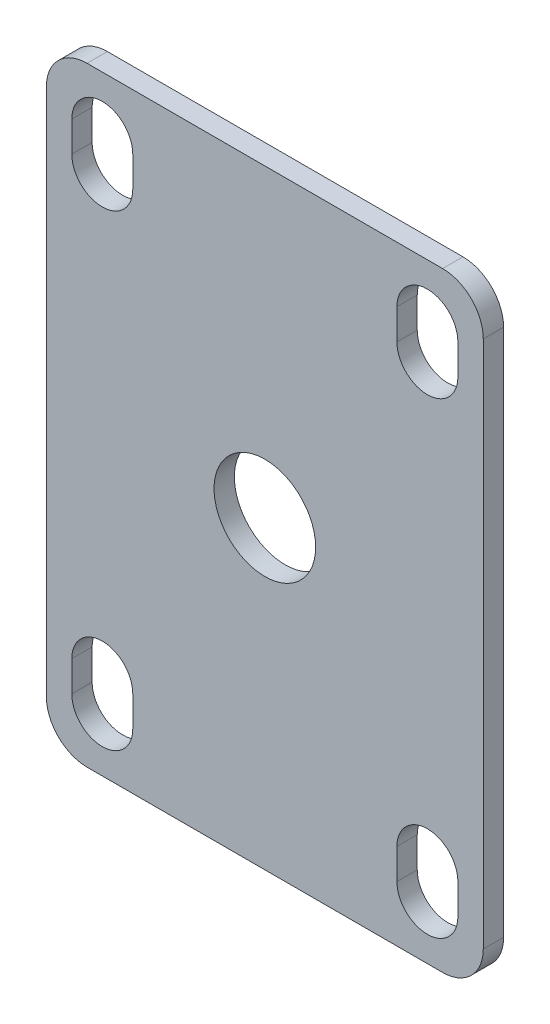
SolidWorks part; units mm, degrees
ref_plane "Front Plane" through (0, 0, 0) normal (0, 0, 1) x (1, 0, 0)
ref_plane "Top Plane" through (0, 0, 0) normal (0, 1, 0) x (1, 0, 0)
ref_plane "Right Plane" through (0, 0, 0) normal (1, 0, 0) x (0, 0, -1)
sketch "Sketch1" plane through (0, 0, 0) normal (0, 0, 1) x (1, 0, 0)
  line L0 (37.5, 8.5) -> (37.5, 5.5) construction
  line L1 (4, 0) -> (39, 0)
  line L2 (0, 4) -> (0, 56)
  line L3 (4, 60) -> (39, 60)
  line L4 (43, 4) -> (43, 56)
  line L5 (40.5, 8.5) -> (40.5, 5.5)
  line L6 (34.5, 8.5) -> (34.5, 5.5)
  line L7 (43, 30) -> (0, 30) construction
  line L8 (21.5, 60) -> (21.5, 0) construction
  line L9 (37.5, 51.5) -> (37.5, 54.5) construction
  line L10 (40.5, 51.5) -> (40.5, 54.5)
  line L11 (34.5, 51.5) -> (34.5, 54.5)
  line L12 (5.5, 8.5) -> (5.5, 5.5) construction
  line L13 (2.5, 8.5) -> (2.5, 5.5)
  line L14 (8.5, 8.5) -> (8.5, 5.5)
  line L15 (5.5, 51.5) -> (5.5, 54.5) construction
  line L16 (2.5, 51.5) -> (2.5, 54.5)
  line L17 (8.5, 51.5) -> (8.5, 54.5)
  circle A0 centre (21.5, 30) radius 5
  arc A1 (40.5, 8.5) -> (34.5, 8.5) centre (37.5, 8.5) ccw
  arc A2 (34.5, 5.5) -> (40.5, 5.5) centre (37.5, 5.5) ccw
  arc A3 (40.5, 51.5) -> (34.5, 51.5) centre (37.5, 51.5) cw
  arc A4 (34.5, 54.5) -> (40.5, 54.5) centre (37.5, 54.5) cw
  arc A5 (2.5, 8.5) -> (8.5, 8.5) centre (5.5, 8.5) cw
  arc A6 (8.5, 5.5) -> (2.5, 5.5) centre (5.5, 5.5) cw
  arc A7 (2.5, 51.5) -> (8.5, 51.5) centre (5.5, 51.5) ccw
  arc A8 (8.5, 54.5) -> (2.5, 54.5) centre (5.5, 54.5) ccw
  arc A9 (39, 0) -> (43, 4) centre (39, 4) ccw
  arc A10 (4, 0) -> (0, 4) centre (4, 4) cw
  arc A11 (0, 56) -> (4, 60) centre (4, 56) cw
  arc A12 (39, 60) -> (43, 56) centre (39, 56) cw
  point P9 (37.5, 7)
  point P14 (37.5, 11.5)
  point P15 (37.5, 2.5)
  point P18 (21.5, 60)
  point P19 (43, 30)
  point P24 (37.5, 53)
  point P31 (5.5, 7)
  point P38 (5.5, 53)
  point P45 (43, 0)
  point P48 (0, 0)
  point P53 (43, 60)
  dimension "D3" = 10
  dimension "D8" = 4
  dimension "D1" = 60
  dimension "D2" = 43
  dimension "D4" = 6
  dimension "D5" = 9
  dimension "D6" = 2.5
  dimension "D7" = 2.5
extrude "Boss-Extrude1" add sketch "Sketch1" along normal blind 2
sketch "Sketch2" plane through (0, 0, 2) normal (0, 0, 1) x (1, 0, 0)
  circle A0 centre (37.5, 53) radius 3 construction
  circle A1 centre (5.5, 7) radius 3 construction
